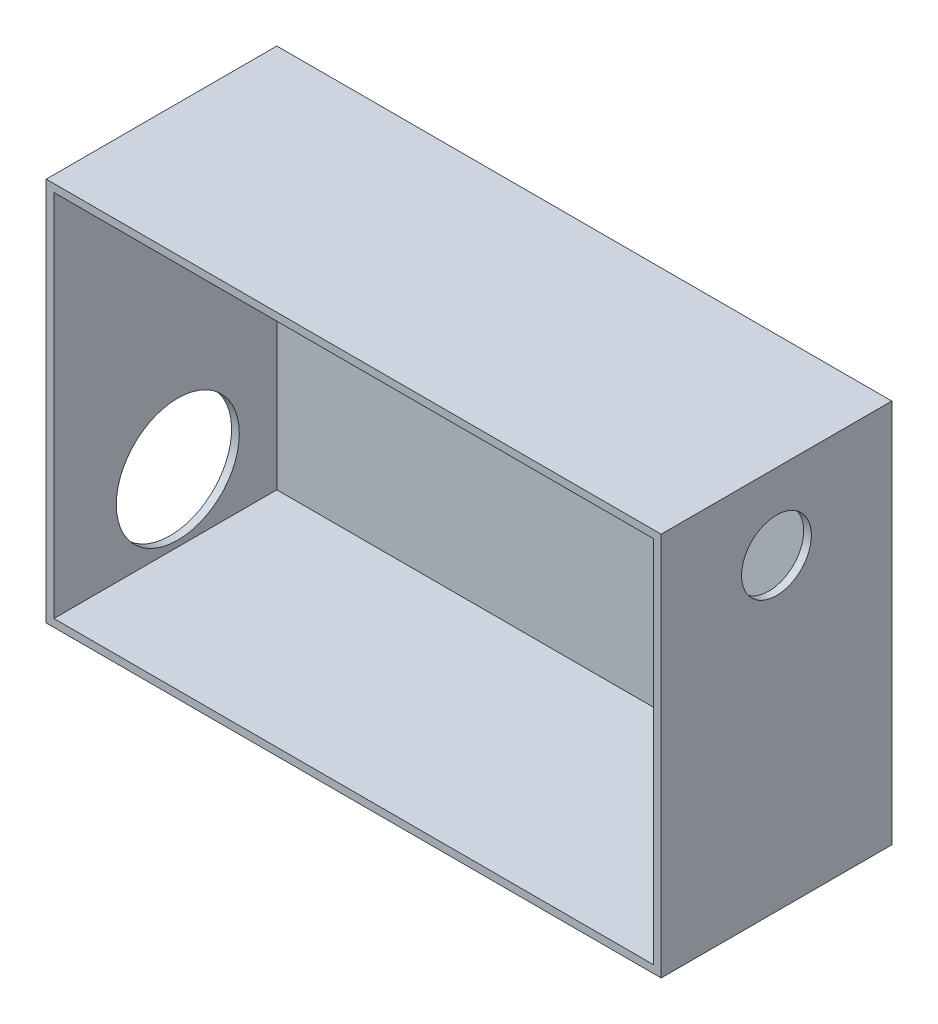
SolidWorks part; units mm, degrees
ref_plane "前视基准面" through (0, 0, 0) normal (0, 0, 1) x (1, 0, 0)
ref_plane "上视基准面" through (0, 0, 0) normal (0, 1, 0) x (1, 0, 0)
ref_plane "右视基准面" through (0, 0, 0) normal (1, 0, 0) x (0, 0, -1)
other "Configuration Table"
sketch "草图1" plane through (0, 0, 0) normal (0, 0, 1) x (1, 0, 0)
  line L1 (-40, 25) -> (40, 25)
  line L2 (-40, 25) -> (-40, -25)
  line L3 (-40, -25) -> (40, -25)
  line L4 (40, 25) -> (40, -25)
  line L5 (-40, 25) -> (40, -25) construction
  line L6 (-40, -25) -> (40, 25) construction
  point P0 (0, 0)
  dimension "D1" = 50
  dimension "D2" = 80
extrude "凸台-拉伸1" add sketch "草图1" along normal blind 30
shell "抽壳1" thickness 1
sketch "草图3" plane through (40, 0, 0) normal (1, 0, 0) x (0, 0, -1)
  line L0 (-15, 25) -> (-15, -25) construction
  line L1 (-30, 25) -> (0, 25) construction
  line L2 (-30, -25) -> (0, -25) construction
  line L3 (-15, -25) -> (-15, 0.6473) construction
  circle A0 centre (-15, 15.1173) radius 4.5395
extrude "切除-拉伸1" cut sketch "草图3" against normal blind 30
sketch "草图4" plane through (-40, 0, 0) normal (-1, 0, 0) x (0, 0, 1)
  circle A0 centre (13.8815, -15.2291) radius 8
  point P2 (13.8815, -15.2291)
  dimension "D1" = 16
extrude "切除-拉伸2" cut sketch "草图4" against normal blind 30
